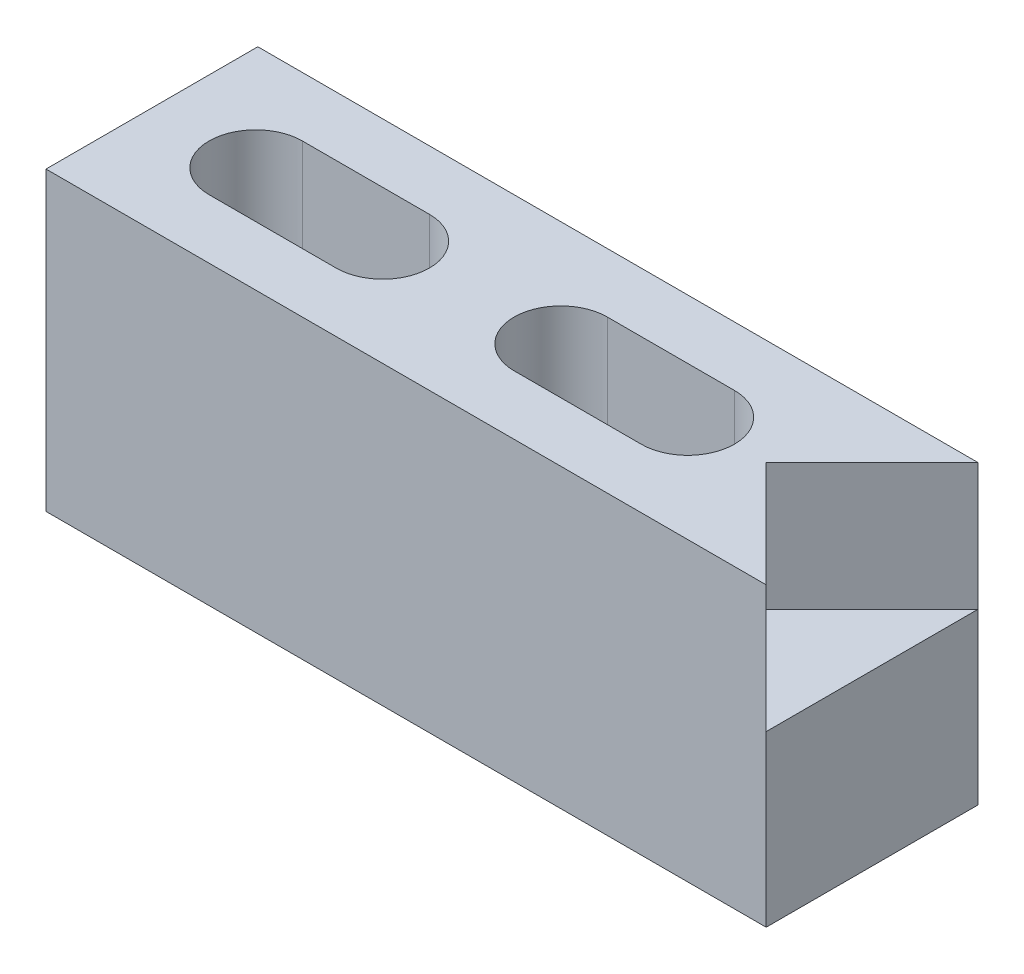
SolidWorks part; units mm, degrees
ref_plane "Front Plane" through (0, 0, 0) normal (0, 0, 1) x (1, 0, 0)
ref_plane "Top Plane" through (0, 0, 0) normal (0, 1, 0) x (1, 0, 0)
ref_plane "Right Plane" through (0, 0, 0) normal (1, 0, 0) x (0, 0, -1)
sketch "Sketch1" plane through (0, 0, 0) normal (0, 0, 1) x (1, 0, 0)
  line L0 (0, 0) -> (43.18, 0)
  line L6 (0, 0) -> (0, 17.78)
  line L10 (0, 17.78) -> (43.18, 17.78)
  line L11 (43.18, 0) -> (43.18, 17.78)
  dimension "D1" = 43.18
  dimension "D2" = 17.78
extrude "Boss-Extrude1" add sketch "Sketch1" against normal blind 12.7
sketch "Sketch3" plane through (0, 17.78, 0) normal (0, 1, 0) x (1, 0, 0)
  line L0 (43.18, 12.7) -> (36.83, 6.35)
  line L1 (36.83, 6.35) -> (43.18, 0)
  line L4 (43.18, 12.7) -> (43.18, 0)
  dimension "D2" = 90
extrude "Cut-Extrude1" cut sketch "Sketch3" against normal blind 7.62
sketch "Sketch4" plane through (0, 17.78, 0) normal (0, 1, 0) x (1, 0, 0)
  line L0 (32.131, 6.35) -> (24.511, 6.35) construction
  line L1 (32.131, 3.556) -> (24.511, 3.556)
  line L2 (32.131, 9.144) -> (24.511, 9.144)
  line L3 (13.843, 6.35) -> (6.223, 6.35) construction
  line L4 (13.843, 3.556) -> (6.223, 3.556)
  line L5 (13.843, 9.144) -> (6.223, 9.144)
  line L6 (43.18, 0) -> (0, 0) construction
  arc A0 (32.131, 3.556) -> (32.131, 9.144) centre (32.131, 6.35) ccw
  arc A1 (24.511, 9.144) -> (24.511, 3.556) centre (24.511, 6.35) ccw
  arc A2 (13.843, 3.556) -> (13.843, 9.144) centre (13.843, 6.35) ccw
  arc A3 (6.223, 9.144) -> (6.223, 3.556) centre (6.223, 6.35) ccw
  point P2 (28.321, 6.35)
  point P7 (10.033, 6.35)
  point P14 (34.925, 6.35)
  point P18 (16.637, 6.35)
  point P19 (21.717, 6.35)
  dimension "D1" = 2.794
  dimension "D2" = 1.905
  dimension "D3" = 7.62
  dimension "D4" = 6.35
  dimension "D5" = 5.08
extrude "Cut-Extrude2" cut sketch "Sketch4" against normal through all
